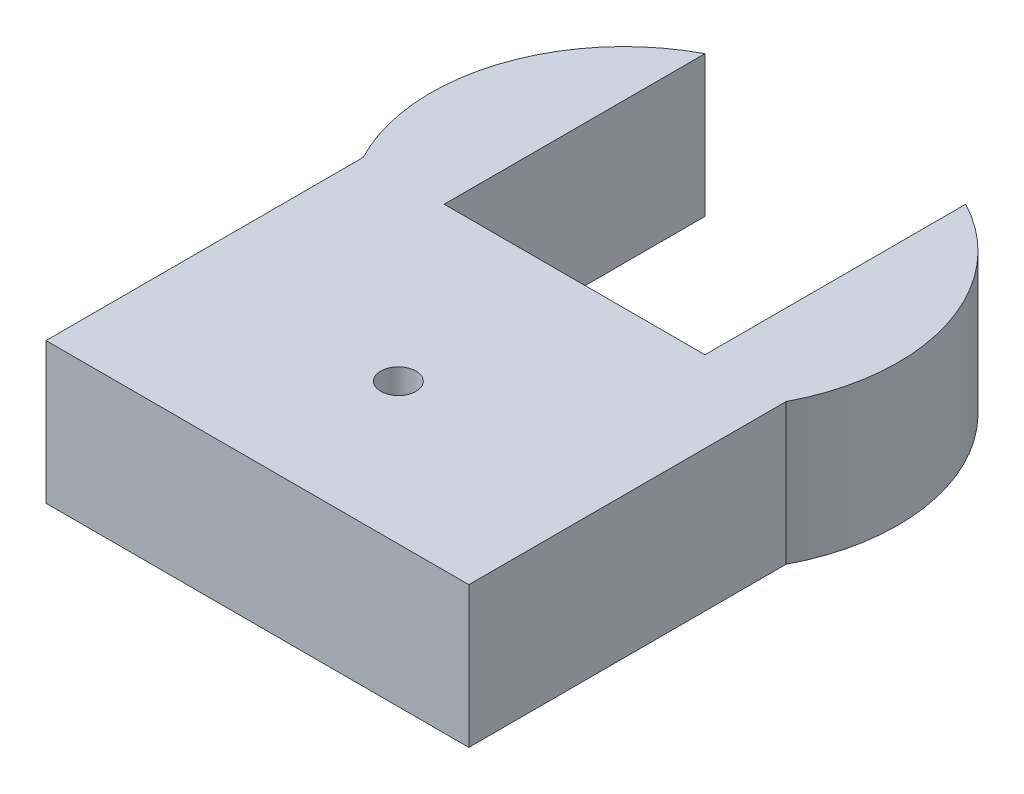
SolidWorks part; units mm, degrees
ref_plane "Front Plane" through (0, 0, 0) normal (0, 0, 1) x (1, 0, 0)
ref_plane "Top Plane" through (0, 0, 0) normal (0, 1, 0) x (1, 0, 0)
ref_plane "Right Plane" through (0, 0, 0) normal (1, 0, 0) x (0, 0, -1)
sketch "Sketch1" plane through (0, 0, 0) normal (0, 1, 0) x (1, 0, 0)
  line L0 (-19.8017, 0) -> (17.1983, 0)
  line L1 (-19.8017, 0) -> (-19.8017, 37)
  line L2 (17.1983, 0) -> (17.1983, 37)
  line L3 (-19.8017, 0) -> (-31.3017, 0) construction
  line L4 (17.1983, 0) -> (5.5712, 0) construction
  line L8 (17.1983, 0) -> (28.6983, 0) construction
  line L9 (-31.3017, 0) -> (-31.3017, -45)
  line L10 (-31.3017, -45) -> (28.6983, -45)
  line L11 (28.6983, -45) -> (28.6983, 0)
  arc A4 (-19.8017, 37) -> (-31.3017, 0) centre (-7.0517, 12.75) ccw
  arc A5 (17.1983, 37) -> (28.6983, 0) centre (4.4483, 12.75) cw
extrude "Boss-Extrude1" add sketch "Sketch1" along normal blind 20
sketch "Sketch2" plane through (0, 20, 0) normal (0, 1, 0) x (1, 0, 0)
  line L0 (-1.3017, -45) -> (-1.3017, -5) construction
  line L2 (-31.3017, -45) -> (28.6983, -45) construction
  circle A1 centre (-1.3017, -25) radius 2.5
extrude "Cut-Extrude1" cut sketch "Sketch2" against normal blind 20
